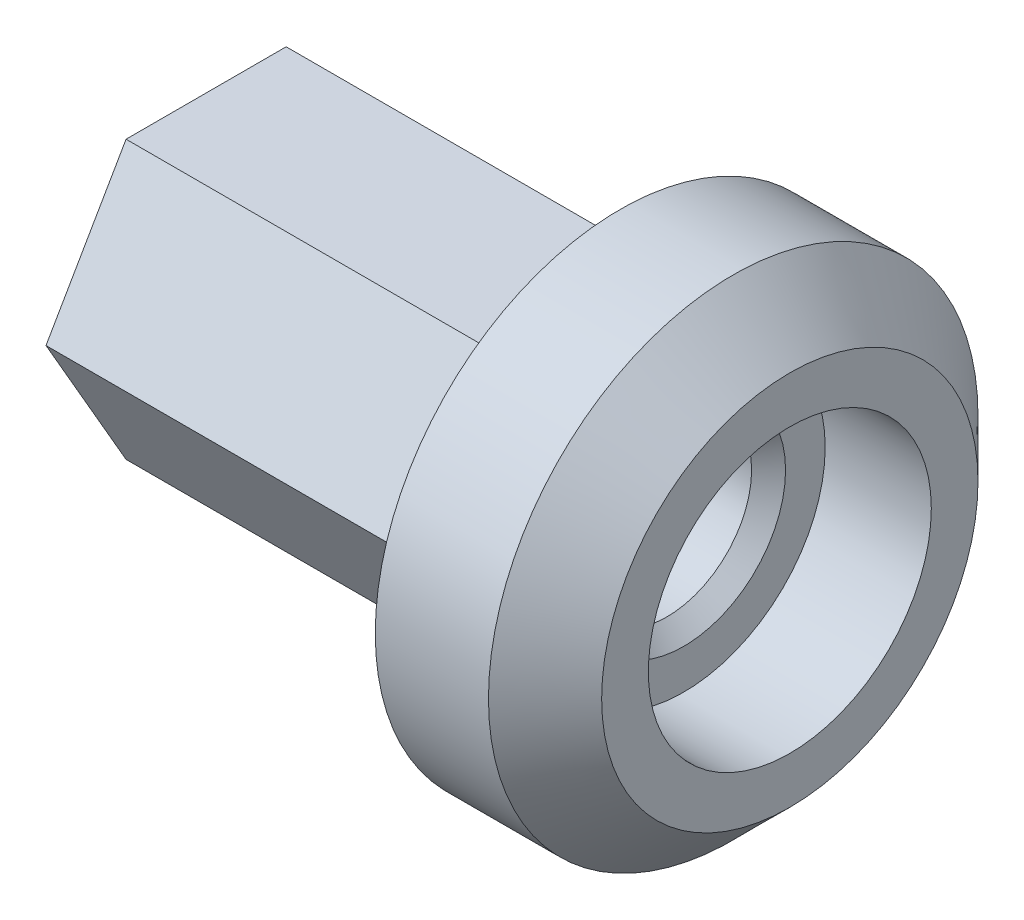
SolidWorks part; units mm, degrees
ref_plane "Front Plane" through (0, 0, 0) normal (0, 0, 1) x (1, 0, 0)
ref_plane "Top Plane" through (0, 0, 0) normal (0, 1, 0) x (1, 0, 0)
ref_plane "Right Plane" through (0, 0, 0) normal (1, 0, 0) x (0, 0, -1)
sketch "Sketch1" plane through (0, 0, 0) normal (1, 0, 0) x (0, 0, -1)
  line L1 (3.5929, 6.223) -> (-3.5929, 6.223)
  line L2 (-3.5929, 6.223) -> (-7.1857, 0)
  line L3 (-7.1857, 0) -> (-3.5929, -6.223)
  line L4 (-3.5929, -6.223) -> (3.5929, -6.223)
  line L5 (3.5929, -6.223) -> (7.1857, 0)
  line L6 (7.1857, 0) -> (3.5929, 6.223)
  circle A0 centre (0, 0) radius 6.223 construction
  circle A1 centre (0, 0) radius 3.81
  dimension "D1" = 12.446
  dimension "D2" = 7.62
extrude "Boss-Extrude1" add sketch "Sketch1" against normal offset from surface (18.5775 mm away) 1.27
sketch "Sketch2" plane through (0, 0, 0) normal (1, 0, 0) x (0, 0, -1)
  line L0 (3.5929, 6.223) -> (-3.5929, 6.223) construction
  circle A0 centre (0, 0) radius 10.9855
  circle A1 centre (0, 0) radius 6.223 construction
  circle A2 centre (0, 0) radius 3.81
  circle A3 centre (0, 0) radius 3.81 construction
  dimension "D1" = 4.7625
extrude "Boss-Extrude2" add sketch "Sketch2" along normal blind 7.62
sketch "Sketch3" plane through (7.62, 0, 0) normal (1, 0, 0) x (0, 0, -1)
  circle A0 centre (0, 0) radius 6.35
  dimension "D1" = 12.7
extrude "Cut-Extrude1" cut sketch "Sketch3" against normal blind 4.7625
chamfer "Chamfer1" distance 2.54 angle 45 1 edges at (7.62, 0, -10.9855)
chamfer "Chamfer2" distance 0.762 angle 45 2 edges at (2.8575, 0, -3.81) (-18.5775, 0, 3.81)
